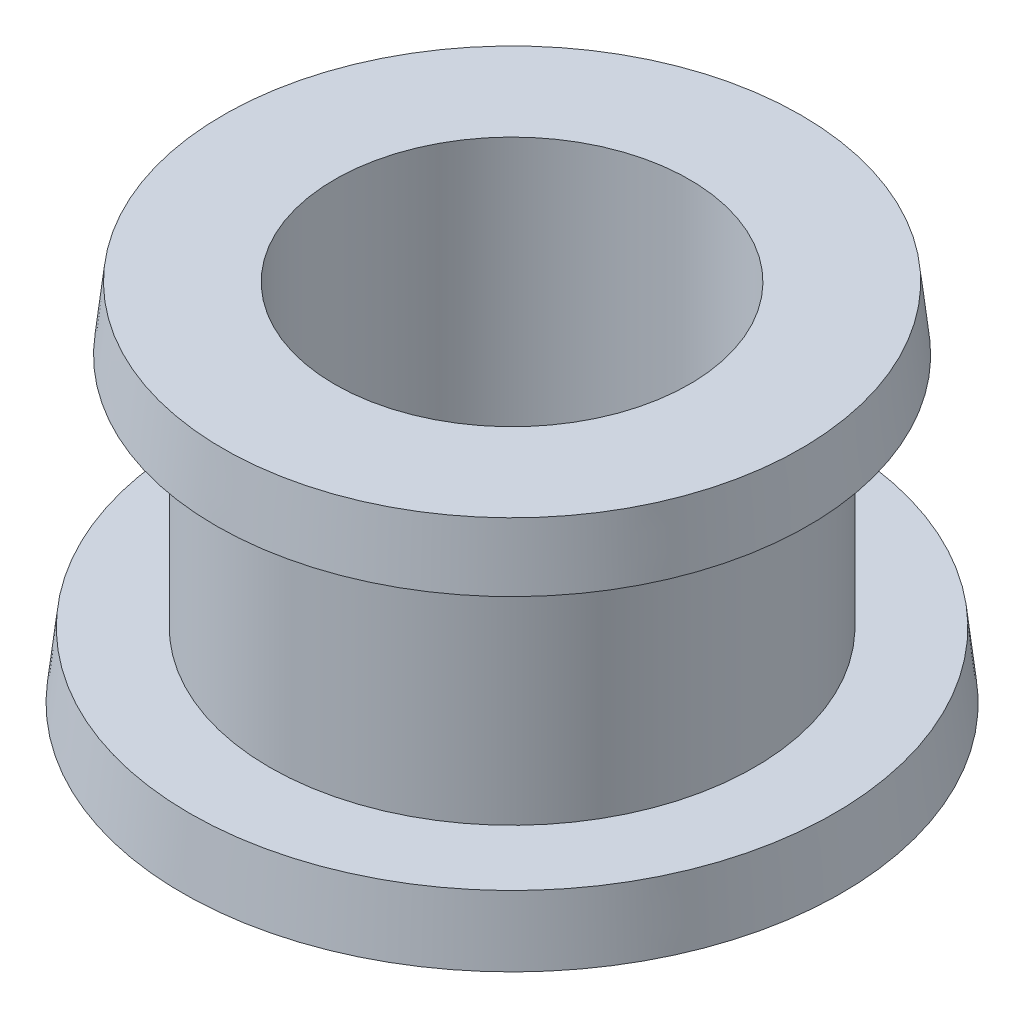
SolidWorks part; units mm, degrees
material "橡胶"
ref_plane "前视基准面" through (0, 0, 0) normal (0, 0, 1) x (1, 0, 0)
ref_plane "上视基准面" through (0, 0, 0) normal (0, 1, 0) x (1, 0, 0)
ref_plane "右视基准面" through (0, 0, 0) normal (1, 0, 0) x (0, 0, -1)
other "Configuration Table"
sketch "草图1" plane through (0, 0, 0) normal (0, 0, 1) x (1, 0, 0)
  line L0 (0, 0) -> (0, 14758.2211) construction
  line L1 (0, 2.8568) -> (2.443, 2.8568)
  line L2 (2.443, 2.8568) -> (2.5026, 2.3217)
  line L3 (2.5026, 2.3217) -> (2.0497, 2.3217)
  line L4 (2.0497, 2.3217) -> (2.0497, 0.327)
  line L5 (2.0497, 0.327) -> (2.7249, 0.327)
  line L6 (2.7249, 0.327) -> (2.7865, -0.2256)
  line L7 (2.7865, -0.2256) -> (0, -0.2256)
  line L8 (0, 2.8568) -> (0, -0.2256)
  point P5 (5.4042, -3.2191)
  point P12 (3.4378, 5.6059)
  point P13 (0, 2.9493)
  point P14 (0, 0)
  point P15 (0, 2.8665)
  point P16 (2.443, 2.8568)
  point P17 (2.7865, -0.2256)
revolve "旋转1" add sketch "草图1" angle 360 about L0
sketch "草图2" plane through (0, 2.8568, 0) normal (0, 1, 0) x (1, 0, 0)
  circle A0 centre (0, 0) radius 1.5
  dimension "D1" = 3
extrude "切除-拉伸1" cut sketch "草图2" against normal through all
